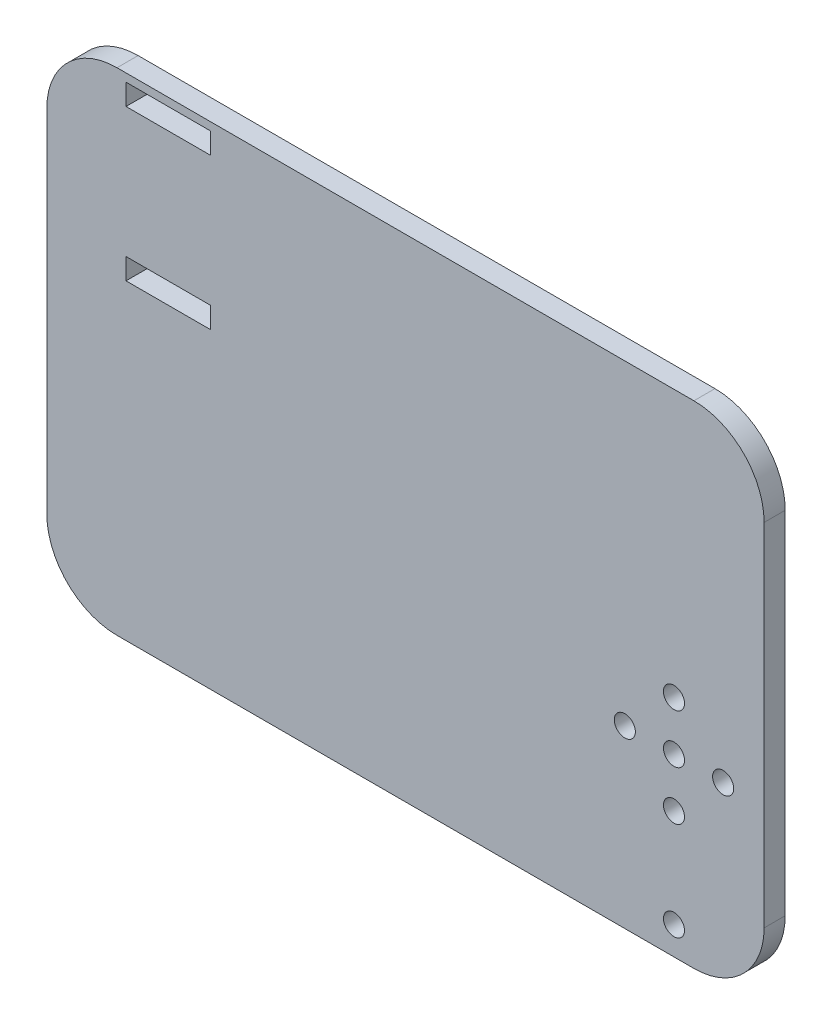
SolidWorks part; units mm, degrees
ref_plane "Front Plane" through (0, 0, 0) normal (0, 0, 1) x (1, 0, 0)
ref_plane "Top Plane" through (0, 0, 0) normal (0, 1, 0) x (1, 0, 0)
ref_plane "Right Plane" through (0, 0, 0) normal (1, 0, 0) x (0, 0, -1)
sketch "Sketch1" plane through (0, 0, 0) normal (0, 0, 1) x (1, 0, 0)
  line L0 (31.225, 95) -> (31.225, -95)
  circle A0 centre (0, 0) radius 100
  dimension "D1" = 200
  dimension "D2" = 190
extrude "Boss-Extrude1" add sketch "Sketch1" along normal blind 3 contours L0 A0
sketch "Sketch2" plane through (0, 0, 3) normal (0, 0, 1) x (1, 0, 0)
  line L0 (-118.5312, 0) -> (41.1189, 0) construction
sketch "Sketch3" plane through (0, 0, 3) normal (0, 0, 1) x (1, 0, 0)
  line L0 (-118.5312, 0) -> (41.1189, 0) construction
  line L1 (-100, 45) -> (31.225, 45)
  line L2 (-100, 45) -> (-100, -25)
  line L3 (-100, -25) -> (31.225, -25)
  line L4 (31.225, 45) -> (31.225, -25)
  line L5 (-100, 45) -> (31.225, -25) construction
  line L6 (-100, -25) -> (31.225, 45) construction
  line L7 (31.225, 95) -> (31.225, -95) construction
  arc A2 (31.225, 95) -> (31.225, -95) centre (0, 0) ccw construction
  point P0 (-34.3875, 10)
  dimension "D1" = 45
  dimension "D2" = 25
extrude "Cut-Extrude2" cut sketch "Sketch3" against normal blind 10 flip side to cut
sketch "Sketch4" plane through (0, 0, 3) normal (0, 0, 1) x (1, 0, 0)
  line L0 (-118.5312, 0) -> (41.1189, 0) construction
  circle A0 centre (0, 7) radius 1.5
  circle A1 centre (0, -7) radius 1.5
  circle A2 centre (7, 0) radius 1.5
  circle A3 centre (-7, 0) radius 1.5
  circle A4 centre (0, 0) radius 1.5
  circle A5 centre (0, -21) radius 1.5
  point P15 (0, 0)
  dimension "D1" = 3
  dimension "D2" = 3
  dimension "D3" = 3
  dimension "D4" = 3
  dimension "D9" = 3
  dimension "D10" = 3
  dimension "D5" = 14
  dimension "D6" = 7
  dimension "D7" = 14
  dimension "D8" = 7
  dimension "D11" = 21
extrude "Cut-Extrude3" cut sketch "Sketch4" against normal up to next
sketch "Sketch5" plane through (0, 0, 3) normal (0, 0, 1) x (1, 0, 0)
  line L0 (-118.5312, 0) -> (41.1189, 0) construction
  line L1 (12.8361, 45) -> (60.9901, 45)
  line L2 (12.8361, 45) -> (12.8361, -45)
  line L3 (12.8361, -45) -> (60.9901, -45)
  line L4 (60.9901, 45) -> (60.9901, -45)
  line L5 (12.8361, 45) -> (60.9901, -45) construction
  line L6 (12.8361, -45) -> (60.9901, 45) construction
  line L7 (31.225, 45) -> (-89.3029, 45) construction
  point P0 (36.9131, 0)
extrude "Cut-Extrude4" cut sketch "Sketch5" against normal up to next
sketch "Sketch6" plane through (0, 0, 3) normal (0, 0, 1) x (1, 0, 0)
  line L1 (-105.9956, 45) -> (-89.3029, 45)
  line L2 (-105.9956, 45) -> (-105.9956, -45.4854)
  line L3 (-105.9956, -45.4854) -> (-89.3029, -45.4854)
  line L4 (-89.3029, 45) -> (-89.3029, -45.4854)
  line L5 (-105.9956, 45) -> (-89.3029, -45.4854) construction
  line L6 (-105.9956, -45.4854) -> (-89.3029, 45) construction
  point P0 (-97.6492, -0.2427)
extrude "Cut-Extrude5" cut sketch "Sketch6" against normal up to next
fillet "Fillet1" radius 10 4 edges at (-89.3029, 45, 1.5) (12.8361, 45, 1.5) (12.8361, -25, 1.5) (-89.3029, -25, 1.5)
sketch "Sketch8" plane through (0, 0, 3) normal (0, 0, 1) x (1, 0, 0)
  line L1 (-66.0239, 43.8593) -> (-78.0239, 43.8593)
  line L2 (-66.0239, 43.8593) -> (-66.0239, 40.8593)
  line L3 (-66.0239, 40.8593) -> (-78.0239, 40.8593)
  line L4 (-78.0239, 43.8593) -> (-78.0239, 40.8593)
  line L5 (-66.0239, 43.8593) -> (-78.0239, 40.8593) construction
  line L6 (-66.0239, 40.8593) -> (-78.0239, 43.8593) construction
  line L7 (-66.0239, 22.3593) -> (-78.0239, 22.3593)
  line L8 (-66.0239, 22.3593) -> (-66.0239, 19.3593)
  line L9 (-66.0239, 19.3593) -> (-78.0239, 19.3593)
  line L10 (-78.0239, 22.3593) -> (-78.0239, 19.3593)
  line L11 (-66.0239, 22.3593) -> (-78.0239, 19.3593) construction
  line L12 (-66.0239, 19.3593) -> (-78.0239, 22.3593) construction
  point P0 (-72.0239, 42.3593)
  point P5 (-72.0239, 20.8593)
  point P15 (-72.0239, 40.8593)
  dimension "D1" = 12
  dimension "D2" = 18.5
  dimension "D3" = 3
  dimension "D4" = 3
extrude "Cut-Extrude6" cut sketch "Sketch8" against normal up to next
